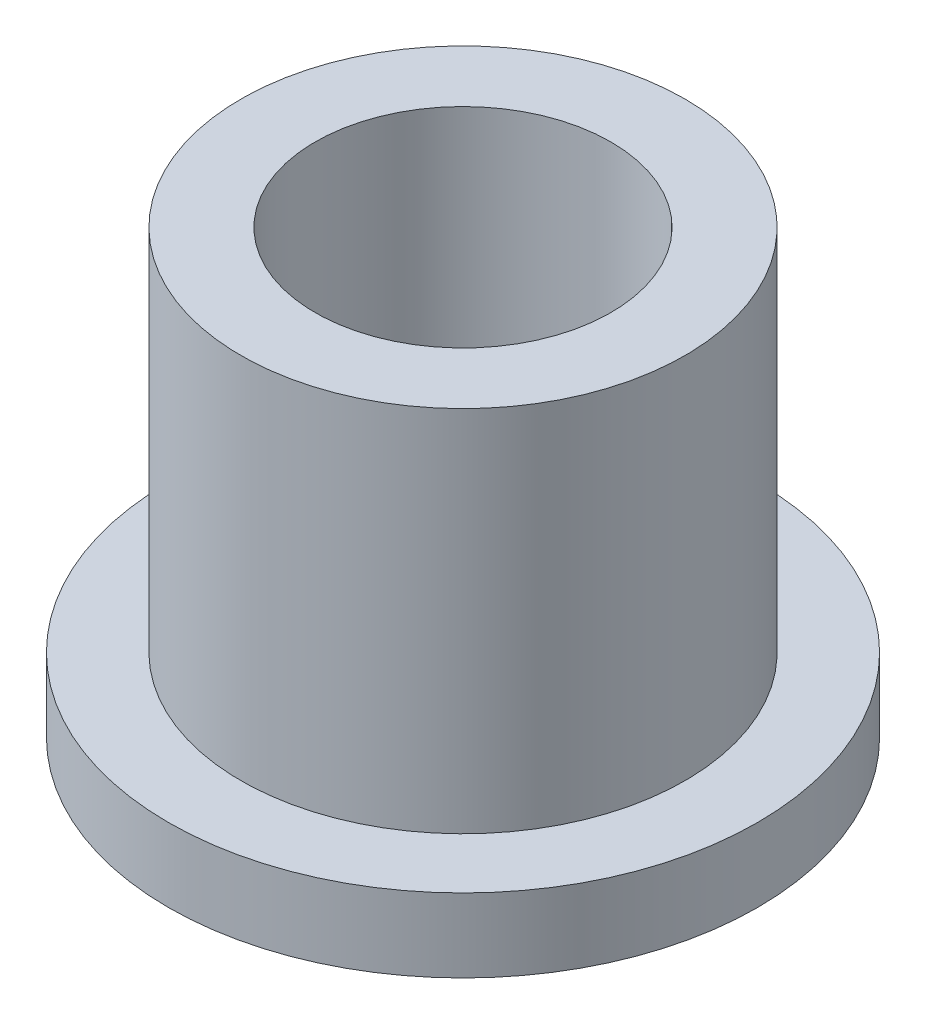
SolidWorks part; units mm, degrees
ref_plane "Front" through (0, 0, 0) normal (0, 0, 1) x (1, 0, 0)
ref_plane "Top" through (0, 0, 0) normal (0, 1, 0) x (1, 0, 0)
ref_plane "Right" through (0, 0, 0) normal (1, 0, 0) x (0, 0, -1)
sketch "Sketch1" plane through (0, 0, 0) normal (0, 1, 0) x (1, 0, 0)
  circle A0 centre (0, 0) radius 3.1877
  circle A1 centre (0, 0) radius 4.7879
  circle A2 centre (0, 0) radius 6.35
  dimension "ID" = 6.3754
  dimension "OD" = 9.5758
  dimension "FlangeOD" = 12.7
sketch "Sketch2" plane through (0, 0, 0) normal (0, 1, 0) x (1, 0, 0)
  circle A0 centre (0, 0) radius 3.1877 construction
  circle A1 centre (0, 0) radius 4.7879 construction
  circle A2 centre (0, 0) radius 3.1877
  circle A3 centre (0, 0) radius 4.7879
extrude "Boss-Extrude1" add sketch "Sketch2" along normal blind 9.525
sketch "Sketch3" plane through (0, 0, 0) normal (0, 1, 0) x (1, 0, 0)
  circle A0 centre (0, 0) radius 6.35 construction
  circle A1 centre (0, 0) radius 4.7879 construction
  circle A2 centre (0, 0) radius 6.35
  circle A3 centre (0, 0) radius 4.7879
extrude "Boss-Extrude2" add sketch "Sketch3" along normal blind 1.5875
